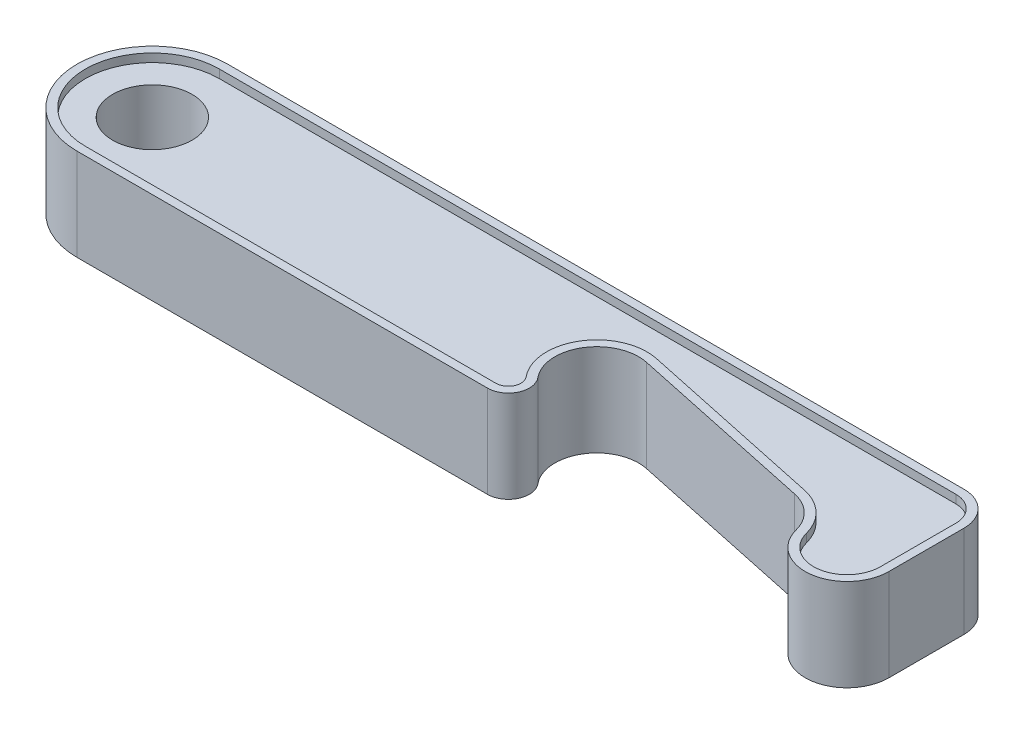
SolidWorks part; units mm, degrees
ref_plane "Płaszczyzna przednia" through (0, 0, 0) normal (0, 0, 1) x (1, 0, 0)
ref_plane "Płaszczyzna górna" through (0, 0, 0) normal (0, 1, 0) x (1, 0, 0)
ref_plane "Płaszczyzna prawa" through (0, 0, 0) normal (1, 0, 0) x (0, 0, -1)
sketch "Szkic1" plane through (0, 0, 0) normal (0, 1, 0) x (1, 0, 0)
  line L0 (-21.2574, 0) -> (4.75, 0) construction
  line L1 (0, 9) -> (88, 9)
  line L2 (0, -9) -> (49.0402, -9)
  line L3 (55.8571, 3.1733) -> (78.3571, -1.6093)
  line L5 (92, 5) -> (92, -4)
  line L6 (43.5552, -9) -> (116.6657, -9) construction
  circle A0 centre (0, 0) radius 4.75
  arc A1 (49.0402, -9) -> (50.966, -4.9058) centre (49.0402, -6.5) ccw
  arc A2 (50.966, -4.9058) -> (55.8571, 3.1733) centre (54.8175, -1.7175) cw
  arc A3 (78.3571, -1.6093) -> (82.1588, -5.25) centre (77.3175, -6.5) cw
  arc A6 (0, 9) -> (0, -9) centre (0, 0) ccw
  arc A7 (82.1588, -5.25) -> (92, -4) centre (87, -4) ccw
  arc A8 (88, 9) -> (92, 5) centre (88, 5) cw
  point P21 (-9, 0)
  point P24 (0, 0)
  dimension "D2" = 9.5
  dimension "D4" = 2.5
  dimension "D6" = 5
  dimension "D7" = 5
  dimension "D9" = 4
  dimension "D10" = 5
  dimension "D1" = 18
  dimension "D3" = 9
  dimension "D5" = 12
  dimension "D8" = 22.5
  dimension "D11" = 101
extrude "Dodanie-wyciągnięcie1" add sketch "Szkic1" along normal blind 9
sketch "Szkic3" plane through (0, 9, 0) normal (0, 1, 0) x (1, 0, 0)
  line L4 (92, -4) -> (92, 5) construction
  line L5 (55.8571, 3.1733) -> (78.3571, -1.6093) construction
  line L6 (0, -9) -> (49.0402, -9) construction
  line L7 (88, 9) -> (0, 9) construction
  line L8 (0, -8) -> (49.0402, -8)
  line L9 (56.065, 4.1514) -> (78.565, -0.6311)
  line L10 (91, -4) -> (91, 5)
  line L11 (88, 8) -> (0, 8)
  line L12 (0, -8) -> (49.0402, -8)
  line L13 (56.065, 4.1514) -> (78.565, -0.6311)
  line L14 (91, -4) -> (91, 5)
  line L15 (88, 8) -> (0, 8)
  line L16 (92, -4) -> (92, 5)
  line L17 (55.8571, 3.1733) -> (78.3571, -1.6093)
  line L18 (0, -9) -> (49.0402, -9)
  line L19 (88, 9) -> (0, 9)
  arc A6 (92, 5) -> (88, 9) centre (88, 5) ccw construction
  arc A7 (82.1588, -5.25) -> (92, -4) centre (87, -4) ccw construction
  arc A8 (82.1588, -5.25) -> (78.3571, -1.6093) centre (77.3175, -6.5) ccw construction
  arc A9 (55.8571, 3.1733) -> (50.966, -4.9058) centre (54.8175, -1.7175) ccw construction
  arc A10 (49.0402, -9) -> (50.966, -4.9058) centre (49.0402, -6.5) ccw construction
  arc A11 (0, 9) -> (0, -9) centre (0, 0) ccw construction
  arc A12 (0, 8) -> (0, -8) centre (0, 0) ccw
  arc A13 (49.0402, -8) -> (50.1957, -5.5435) centre (49.0402, -6.5) ccw
  arc A14 (56.065, 4.1514) -> (50.1957, -5.5435) centre (54.8175, -1.7175) ccw
  arc A15 (83.127, -5) -> (78.565, -0.6311) centre (77.3175, -6.5) ccw
  arc A16 (83.127, -5) -> (91, -4) centre (87, -4) ccw
  arc A17 (91, 5) -> (88, 8) centre (88, 5) ccw
  arc A18 (0, 8) -> (0, -8) centre (0, 0) ccw
  arc A19 (49.0402, -8) -> (50.1957, -5.5435) centre (49.0402, -6.5) ccw
  arc A20 (56.065, 4.1514) -> (50.1957, -5.5435) centre (54.8175, -1.7175) ccw
  arc A21 (83.127, -5) -> (78.565, -0.6311) centre (77.3175, -6.5) ccw
  arc A22 (83.127, -5) -> (91, -4) centre (87, -4) ccw
  arc A23 (91, 5) -> (88, 8) centre (88, 5) ccw
  arc A24 (92, 5) -> (88, 9) centre (88, 5) ccw
  arc A25 (82.1588, -5.25) -> (92, -4) centre (87, -4) ccw
  arc A26 (82.1588, -5.25) -> (78.3571, -1.6093) centre (77.3175, -6.5) ccw
  arc A27 (55.8571, 3.1733) -> (50.966, -4.9058) centre (54.8175, -1.7175) ccw
  arc A28 (49.0402, -9) -> (50.966, -4.9058) centre (49.0402, -6.5) ccw
  arc A29 (0, 9) -> (0, -9) centre (0, 0) ccw
  dimension "D1" = 1
extrude "Dodanie-wyciągnięcie2" add sketch "Szkic3" along normal blind 1
sketch "Szkic4" plane through (0, 0, 0) normal (0, -1, 0) x (1, 0, 0)
  line L4 (55.8571, -3.1733) -> (78.3571, 1.6093) construction
  line L5 (92, 4) -> (92, -5) construction
  line L6 (88, -9) -> (0, -9) construction
  line L7 (0, 9) -> (49.0402, 9) construction
  line L8 (0, -8) -> (88, -8)
  line L9 (91, -5) -> (91, 4)
  line L10 (78.565, 0.6311) -> (56.065, -4.1514)
  line L11 (49.0402, 8) -> (0, 8)
  line L12 (0, -8) -> (88, -8)
  line L13 (91, -5) -> (91, 4)
  line L14 (78.565, 0.6311) -> (56.065, -4.1514)
  line L15 (49.0402, 8) -> (0, 8)
  line L16 (55.8571, -3.1733) -> (78.3571, 1.6093)
  line L17 (92, 4) -> (92, -5)
  line L18 (88, -9) -> (0, -9)
  line L19 (0, 9) -> (49.0402, 9)
  arc A6 (50.966, 4.9058) -> (49.0402, 9) centre (49.0402, 6.5) ccw construction
  arc A7 (50.966, 4.9058) -> (55.8571, -3.1733) centre (54.8175, 1.7175) ccw construction
  arc A8 (78.3571, 1.6093) -> (82.1588, 5.25) centre (77.3175, 6.5) ccw construction
  arc A9 (92, 4) -> (82.1588, 5.25) centre (87, 4) ccw construction
  arc A10 (88, -9) -> (92, -5) centre (88, -5) ccw construction
  arc A11 (0, 9) -> (0, -9) centre (0, 0) ccw construction
  arc A12 (0, 8) -> (0, -8) centre (0, 0) ccw
  arc A13 (88, -8) -> (91, -5) centre (88, -5) ccw
  arc A14 (91, 4) -> (83.127, 5) centre (87, 4) ccw
  arc A15 (78.565, 0.6311) -> (83.127, 5) centre (77.3175, 6.5) ccw
  arc A16 (50.1957, 5.5435) -> (56.065, -4.1514) centre (54.8175, 1.7175) ccw
  arc A17 (50.1957, 5.5435) -> (49.0402, 8) centre (49.0402, 6.5) ccw
  arc A18 (0, 8) -> (0, -8) centre (0, 0) ccw
  arc A19 (88, -8) -> (91, -5) centre (88, -5) ccw
  arc A20 (91, 4) -> (83.127, 5) centre (87, 4) ccw
  arc A21 (78.565, 0.6311) -> (83.127, 5) centre (77.3175, 6.5) ccw
  arc A22 (50.1957, 5.5435) -> (56.065, -4.1514) centre (54.8175, 1.7175) ccw
  arc A23 (50.1957, 5.5435) -> (49.0402, 8) centre (49.0402, 6.5) ccw
  arc A24 (50.966, 4.9058) -> (49.0402, 9) centre (49.0402, 6.5) ccw
  arc A25 (50.966, 4.9058) -> (55.8571, -3.1733) centre (54.8175, 1.7175) ccw
  arc A26 (78.3571, 1.6093) -> (82.1588, 5.25) centre (77.3175, 6.5) ccw
  arc A27 (92, 4) -> (82.1588, 5.25) centre (87, 4) ccw
  arc A28 (88, -9) -> (92, -5) centre (88, -5) ccw
  arc A29 (0, 9) -> (0, -9) centre (0, 0) ccw
  dimension "D1" = 1
extrude "Dodanie-wyciągnięcie3" add sketch "Szkic4" along normal blind 1
